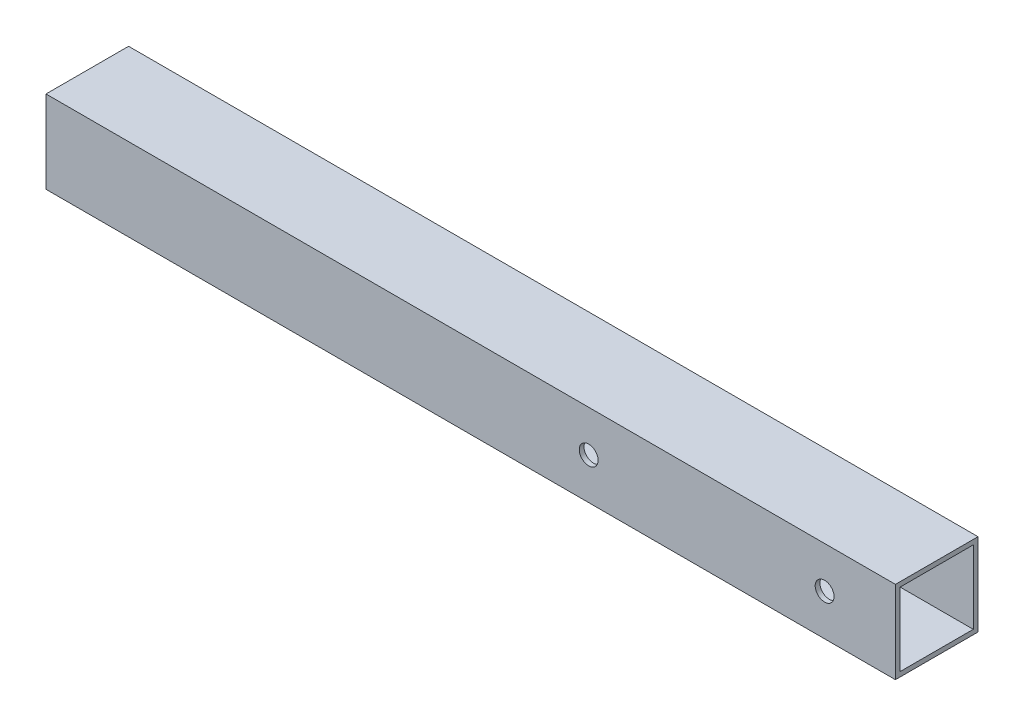
SolidWorks part; units mm, degrees
ref_plane "Front Plane" through (0, 0, 0) normal (0, 0, 1) x (1, 0, 0)
ref_plane "Top Plane" through (0, 0, 0) normal (0, 1, 0) x (1, 0, 0)
ref_plane "Right Plane" through (0, 0, 0) normal (1, 0, 0) x (0, 0, -1)
sketch "Sketch1" plane through (0, 0, 0) normal (1, 0, 0) x (0, 0, -1)
  line L1 (0, 0) -> (35, 0)
  line L2 (0, 0) -> (0, 35)
  line L3 (0, 35) -> (35, 35)
  line L4 (35, 0) -> (35, 35)
  line L5 (2, 2) -> (33, 2)
  line L6 (2, 2) -> (2, 33)
  line L7 (2, 33) -> (33, 33)
  line L8 (33, 2) -> (33, 33)
  dimension "D1" = 35
  dimension "D2" = 35
  dimension "D3" = 2
  dimension "D4" = 2
  dimension "D5" = 2
  dimension "D6" = 2
extrude "Boss-Extrude1" add sketch "Sketch1" along normal blind 360
ref_plane "Plane1" through (0, -100, 0) normal (0, -1, 0) x (-1, 0, 0)
sketch "Sketch2" plane through (0, 0, 0) normal (0, 0, 1) x (1, 0, 0)
  line L2 (360, 35) -> (360, 0) construction
  line L3 (360, 35) -> (0, 35) construction
  circle A0 centre (330, 17.5) radius 4
  circle A1 centre (230, 17.5) radius 4
  dimension "D1" = 8
  dimension "D2" = 8
  dimension "D3" = 100
  dimension "D4" = 30
  dimension "D5" = 17.5
  dimension "D6" = 17.5
extrude "Cut-Extrude1" cut sketch "Sketch2" against normal through all
